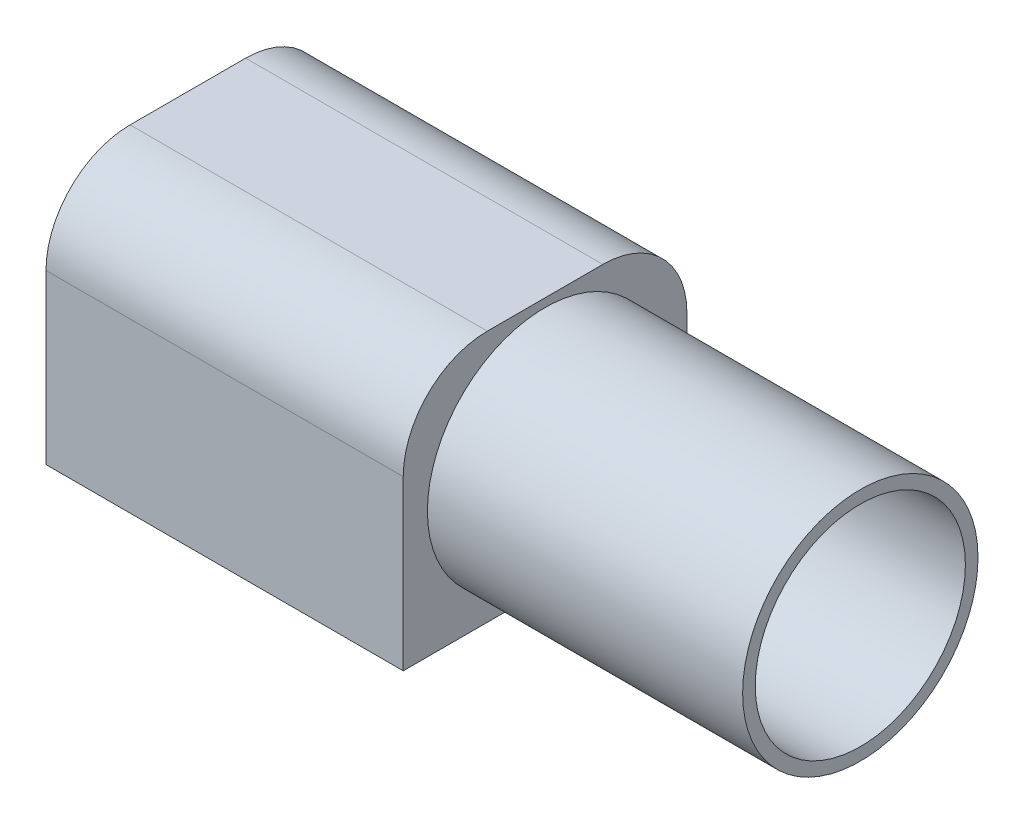
SolidWorks part; units mm, degrees
ref_plane "Front Plane" through (0, 0, 0) normal (0, 0, 1) x (1, 0, 0)
ref_plane "Top Plane" through (0, 0, 0) normal (0, 1, 0) x (1, 0, 0)
ref_plane "Right Plane" through (0, 0, 0) normal (1, 0, 0) x (0, 0, -1)
sketch "Sketch1" plane through (0, 0, 0) normal (0, 1, 0) x (1, 0, 0)
  line L0 (-74.3451, 17.2738) -> (-74.3451, 1.2718) construction
  line L1 (-74.3451, 16.0228) -> (-74.3451, 2.5228)
  line L2 (-74.3451, 16.0228) -> (-57.3451, 16.0228)
  line L3 (-57.3451, 16.0228) -> (-57.3451, 2.5228)
  line L4 (-57.3451, 2.5228) -> (-74.3451, 2.5228)
  point P5 (-74.3451, 9.2728)
  dimension "D1" = 13.5
  dimension "D2" = 17
extrude "Boss-Extrude1" add sketch "Sketch1" along normal blind 12
sketch "Sketch2" plane through (-57.3451, 0, 0) normal (1, 0, 0) x (0, 0, -1)
  line L0 (16.0228, 0) -> (2.5228, 12) construction
  line L2 (16.0228, 12) -> (16.0228, 0) construction
  circle A4 centre (9.2728, 6) radius 5.6
  circle A5 centre (9.2728, 6) radius 5
extrude "Boss-Extrude2" add sketch "Sketch2" along normal blind 15
fillet "Fillet1" radius 4 2 edges at (-65.8451, 12, -2.5228) (-65.8451, 12, -16.0228)
